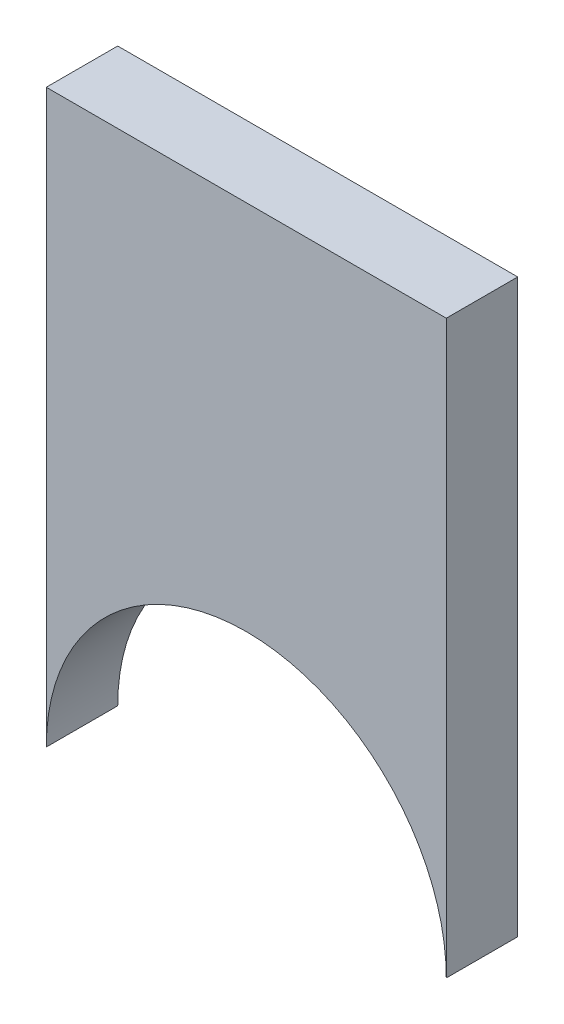
SolidWorks part; units mm, degrees
ref_plane "前视基准面" through (0, 0, 0) normal (0, 0, 1) x (1, 0, 0)
ref_plane "上视基准面" through (0, 0, 0) normal (0, 1, 0) x (1, 0, 0)
ref_plane "右视基准面" through (0, 0, 0) normal (1, 0, 0) x (0, 0, -1)
sketch "草图1" plane through (0, 0, 0) normal (0, 0, 1) x (1, 0, 0)
  line L0 (-56, 0) -> (-56, 160)
  line L1 (56, 0) -> (56, 160)
  line L2 (-56, 160) -> (56, 160)
  arc A1 (56, 0) -> (-56, 0) centre (0, 0) ccw
extrude "凸台-拉伸1" add sketch "草图1" along normal blind 20
